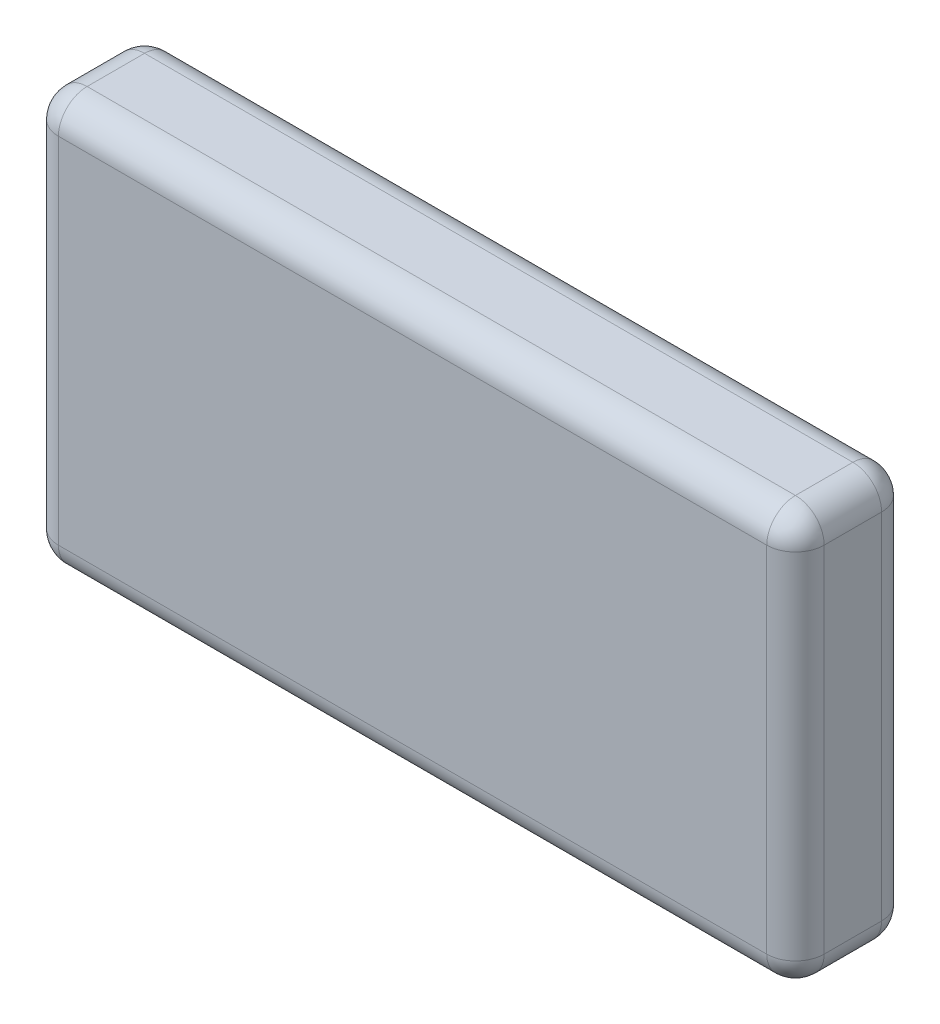
SolidWorks part; units mm, degrees
ref_plane "Front Plane" through (0, 0, 0) normal (0, 0, 1) x (1, 0, 0)
ref_plane "Top Plane" through (0, 0, 0) normal (0, 1, 0) x (1, 0, 0)
ref_plane "Right Plane" through (0, 0, 0) normal (1, 0, 0) x (0, 0, -1)
sketch "Sketch1" plane through (0, 0, 0) normal (0, 0, 1) x (1, 0, 0)
  line L1 (1000, -537.5) -> (-1000, -537.5)
  line L2 (1000, -537.5) -> (1000, 537.5)
  line L3 (1000, 537.5) -> (-1000, 537.5)
  line L4 (-1000, -537.5) -> (-1000, 537.5)
  line L5 (1000, -537.5) -> (-1000, 537.5) construction
  line L6 (1000, 537.5) -> (-1000, -537.5) construction
  point P0 (0, 0)
  dimension "D1" = 1075
  dimension "D2" = 2000
extrude "Boss-Extrude1" add sketch "Sketch1" along normal blind 300
fillet "Fillet1" radius 75 12 edges at (-1000, 0, 300) (-1000, 0, 0) (1000, 0, 0) (1000, 537.5, 150) (1000, 0, 300) (0, 537.5, 0) (-1000, 537.5, 150) (0, 537.5, 300) (-1000, -537.5, 150) (0, -537.5, 300) (1000, -537.5, 150) (0, -537.5, 0)
